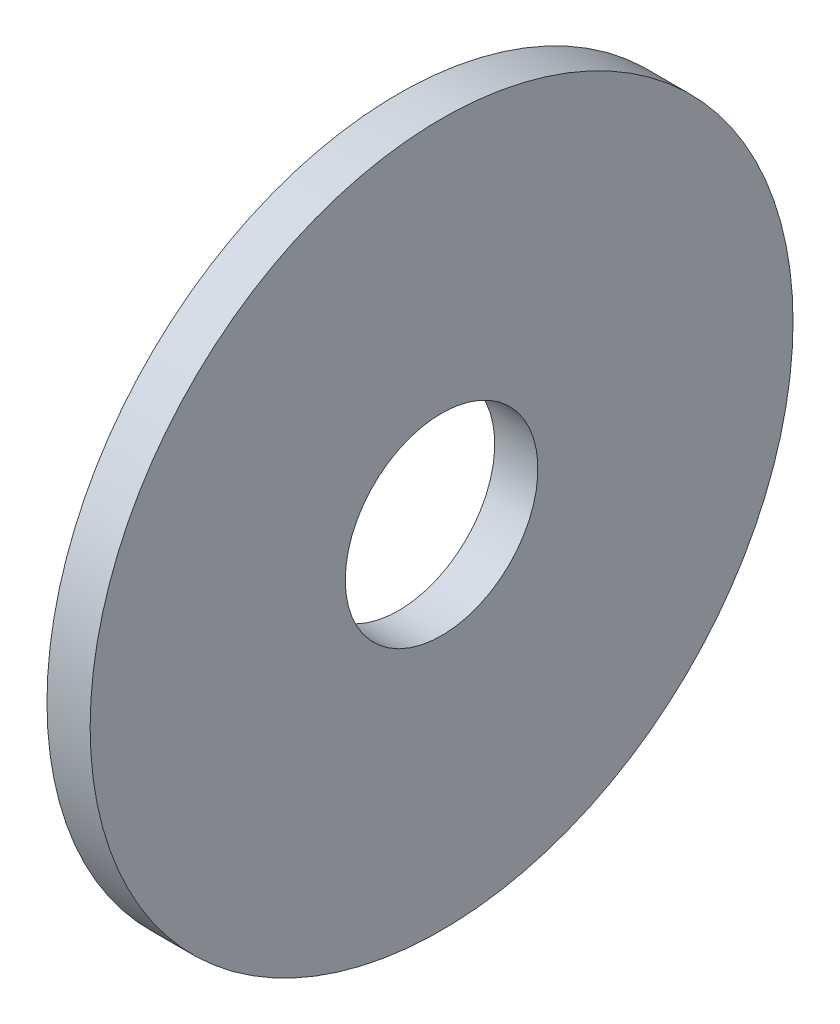
SolidWorks part; units mm, degrees
ref_plane "Plane1" through (0, 0, 0) normal (0, 0, 1) x (1, 0, 0)
ref_plane "Plane2" through (0, 0, 0) normal (0, 1, 0) x (1, 0, 0)
ref_plane "Plane3" through (0, 0, 0) normal (1, 0, 0) x (0, 0, -1)
sketch "Sketch1" plane through (0, 0, 0) normal (0, 0, 1) x (1, 0, 0)
  line L0 (-34.925, 0) -> (9.525, 0) construction
  line L1 (0, 13.4874) -> (0, 49.2125)
  line L2 (0, 49.2125) -> (-6.0452, 49.2125)
  line L3 (-6.0452, 49.2125) -> (-6.0452, 13.4874)
  line L4 (-6.0452, 13.4874) -> (0, 13.4874)
  dimension "Thickness" = 6.0452
  dimension "Inside_dia" = 26.9748
  dimension "Outside_dia" = 98.425
revolve "Base-Revolve" add sketch "Sketch1" angle 360 about L0
